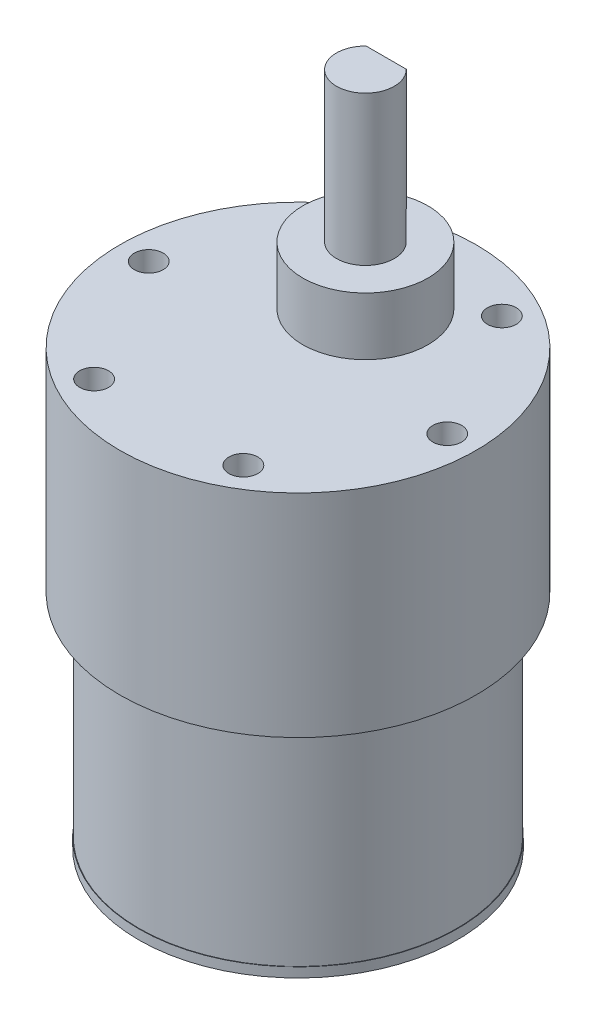
SolidWorks part; units mm, degrees
ref_plane "Front Plane" through (0, 0, 0) normal (0, 0, 1) x (1, 0, 0)
ref_plane "Top Plane" through (0, 0, 0) normal (0, 1, 0) x (1, 0, 0)
ref_plane "Right Plane" through (0, 0, 0) normal (1, 0, 0) x (0, 0, -1)
sketch "Sketch1" plane through (0, 0, 0) normal (0, 1, 0) x (1, 0, 0)
  circle A0 centre (0, 0) radius 18.5
  dimension "D1" = 37
extrude "Boss-Extrude1" add sketch "Sketch1" along normal blind 22
sketch "Sketch2" plane through (0, 0, 0) normal (0, -1, 0) x (1, 0, 0)
  circle A0 centre (0, 0) radius 16.5
  dimension "D1" = 33
extrude "Boss-Extrude2" add sketch "Sketch2" along normal blind 22
sketch "Sketch3" plane through (0, -22, 0) normal (0, -1, 0) x (1, 0, 0)
  circle A0 centre (0, 0) radius 16.55
  dimension "D1" = 33.1
extrude "Boss-Extrude3" add sketch "Sketch3" along normal blind 1
sketch "Sketch4" plane through (0, 22, 0) normal (0, 1, 0) x (1, 0, 0)
  circle A0 centre (0, 7) radius 6.5
  dimension "D1" = 13
  dimension "D2" = 7
extrude "Boss-Extrude4" add sketch "Sketch4" along normal blind 6
sketch "Sketch6" plane through (0, 28, 0) normal (0, 1, 0) x (1, 0, 0)
  circle A0 centre (0, 7) radius 3
  dimension "D1" = 6
extrude "Boss-Extrude5" add sketch "Sketch6" along normal blind 15.5
sketch "Sketch7" plane through (0, 43.5, 0) normal (0, 1, 0) x (1, 0, 0)
  line L0 (-2.0846, 9.1574) -> (2.0846, 9.1574)
  line L1 (-2.0846, 9.1574) -> (-3.0809, 9.1574)
  line L2 (-3.0809, 9.1574) -> (-3.0809, 10.9929)
  line L3 (-3.0809, 10.9929) -> (2.2807, 10.9929)
  line L4 (2.2807, 10.9929) -> (2.2807, 9.1574)
  line L5 (2.2807, 9.1574) -> (2.0846, 9.1574)
  circle A0 centre (0, 7) radius 3 construction
extrude "Cut-Extrude1" cut sketch "Sketch7" against normal blind 12
sketch "Sketch8" plane through (0, 22, 0) normal (0, 1, 0) x (1, 0, 0)
  circle A0 centre (15.5, 0) radius 1.5
  circle A1 centre (7.75, -13.4234) radius 1.5
  circle A2 centre (-7.75, -13.4234) radius 1.5
  circle A3 centre (-15.5, 0) radius 1.5
  circle A4 centre (-7.75, 13.4234) radius 1.5
  circle A5 centre (7.75, 13.4234) radius 1.5
  point P15 (0, 0)
  dimension "D3" = 3
  dimension "D1" = 15.5
  dimension "D2" = 6
extrude "Cut-Extrude2" cut sketch "Sketch8" against normal blind 10
